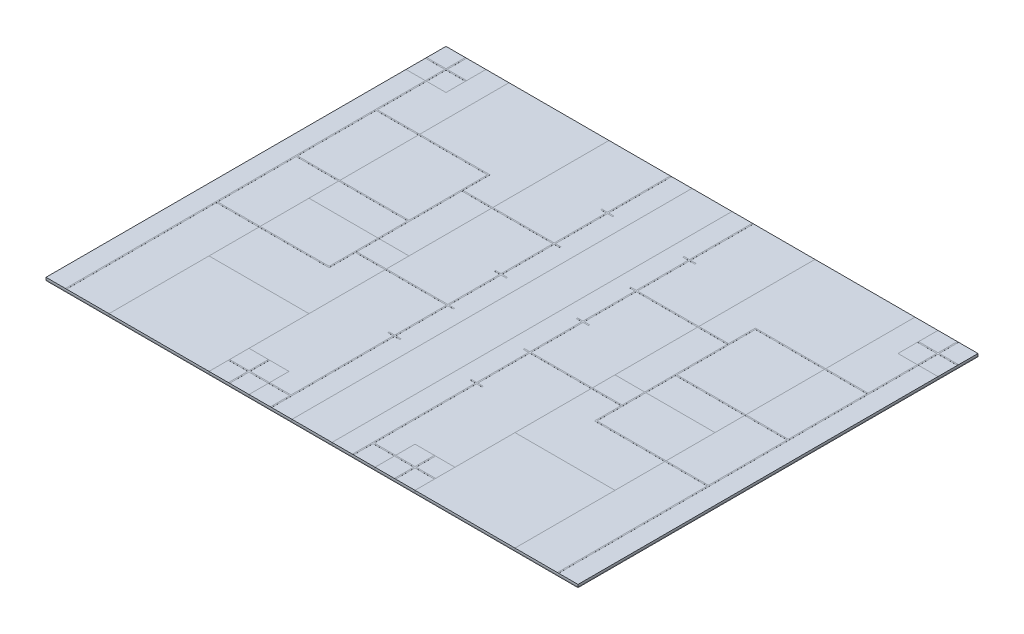
SolidWorks part; units mm, degrees
ref_plane "Front Plane" through (0, 0, 0) normal (0, 0, 1) x (1, 0, 0)
ref_plane "Top Plane" through (0, 0, 0) normal (0, 1, 0) x (1, 0, 0)
ref_plane "Right Plane" through (0, 0, 0) normal (1, 0, 0) x (0, 0, -1)
sketch "Sketch1" plane through (0, 0, 0) normal (0, 1, 0) x (1, 0, 0)
  line L1 (-6650, -5000) -> (6650, -5000)
  line L2 (-6650, -5000) -> (-6650, 5000)
  line L3 (-6650, 5000) -> (6650, 5000)
  line L4 (6650, -5000) -> (6650, 5000)
  line L5 (-6650, -5000) -> (6650, 5000) construction
  line L6 (-6650, 5000) -> (6650, -5000) construction
  point P0 (0, 0)
  dimension "D1" = 13300
  dimension "D2" = 10000
extrude "Boss-Extrude1" add sketch "Sketch1" along normal blind 20
sketch "Sketch3" plane through (0, 20, 0) normal (0, 1, 0) x (1, 0, 0)
  line L0 (6650, 5000) -> (-6650, 5000) construction
  line L1 (-6650, -5000) -> (-5075, -5000)
  line L2 (-6650, -5000) -> (-6650, 5000)
  line L3 (-6650, 5000) -> (-5075, 5000)
  line L4 (-5075, -5000) -> (-5075, 5000)
  dimension "D1" = 1575
extrude "Boss-Extrude2" add sketch "Sketch3" along normal blind 50 separate body
sketch "Sketch7" plane through (0, 20, 0) normal (0, 1, 0) x (1, 0, 0)
  line L1 (-5075, -5000) -> (-2575, -5000)
  line L2 (-5075, -5000) -> (-5075, -2500)
  line L3 (-5075, -2500) -> (-2575, -2500)
  line L4 (-2575, -5000) -> (-2575, -2500)
  dimension "D1" = 2500
  dimension "D2" = 2500
extrude "Boss-Extrude7" add sketch "Sketch7" along normal blind 50 separate body
sketch "Sketch8" plane through (0, 20, 0) normal (0, 1, 0) x (1, 0, 0)
  line L1 (-5075, -2500) -> (-2575, -2500)
  line L2 (-5075, -2500) -> (-5075, 0)
  line L3 (-5075, 0) -> (-2575, 0)
  line L4 (-2575, -2500) -> (-2575, 0)
  dimension "D1" = 2500
  dimension "D2" = 2500
extrude "Boss-Extrude8" add sketch "Sketch8" along normal blind 50 separate body
sketch "Sketch9" plane through (0, 20, 0) normal (0, 1, 0) x (1, 0, 0)
  line L0 (-5075, -5000) -> (-5075, 5000) construction
  line L1 (-5075, 0) -> (-2575, 0)
  line L2 (-5075, 0) -> (-5075, 5000)
  line L3 (-5075, 5000) -> (-2575, 5000)
  line L4 (-2575, 0) -> (-2575, 5000)
  line L5 (6650, 5000) -> (-6650, 5000) construction
  dimension "D1" = 2500
extrude "Boss-Extrude9" add sketch "Sketch9" along normal blind 50 separate body
sketch "Sketch10" plane through (0, 20, 0) normal (0, 1, 0) x (1, 0, 0)
  line L0 (6650, 5000) -> (-6650, 5000) construction
  line L1 (-2575, -5000) -> (-500, -5000)
  line L2 (-2575, -5000) -> (-2575, 5000)
  line L3 (-2575, 5000) -> (-500, 5000)
  line L4 (-500, -5000) -> (-500, 5000)
  dimension "D1" = 2075
extrude "Boss-Extrude10" add sketch "Sketch10" along normal blind 50 separate body
sketch "Sketch11" plane through (0, 20, 0) normal (0, 1, 0) x (1, 0, 0)
  line L0 (-6650, -5000) -> (6650, -5000) construction
  line L1 (-500, 5000) -> (500, 5000)
  line L2 (-500, 5000) -> (-500, -5000)
  line L3 (-500, -5000) -> (500, -5000)
  line L4 (500, 5000) -> (500, -5000)
  dimension "D1" = 1000
extrude "Boss-Extrude12" add sketch "Sketch11" along normal blind 50 separate body
sketch "Sketch12" plane through (0, 20, 0) normal (0, 1, 0) x (1, 0, 0)
  line L0 (-6650, -5000) -> (6650, -5000) construction
  line L1 (500, 5000) -> (2575, 5000)
  line L2 (500, 5000) -> (500, -5000)
  line L3 (500, -5000) -> (2575, -5000)
  line L4 (2575, 5000) -> (2575, -5000)
  dimension "D1" = 2075
extrude "Boss-Extrude13" add sketch "Sketch12" along normal blind 50 separate body
sketch "Sketch13" plane through (0, 20, 0) normal (0, 1, 0) x (1, 0, 0)
  line L1 (2575, 5000) -> (5075, 5000)
  line L2 (2575, 5000) -> (2575, 0)
  line L3 (2575, 0) -> (5075, 0)
  line L4 (5075, 5000) -> (5075, 0)
  dimension "D1" = 2500
  dimension "D2" = 5000
extrude "Boss-Extrude14" add sketch "Sketch13" along normal blind 50 separate body
sketch "Sketch14" plane through (0, 20, 0) normal (0, 1, 0) x (1, 0, 0)
  line L0 (2575, -5000) -> (2575, 5000) construction
  line L1 (2575, 0) -> (5075, 0)
  line L2 (2575, 0) -> (2575, -2500)
  line L3 (2575, -2500) -> (5075, -2500)
  line L4 (5075, 0) -> (5075, -2500)
  dimension "D1" = 2500
  dimension "D2" = 2500
extrude "Boss-Extrude15" add sketch "Sketch14" along normal blind 50 separate body
sketch "Sketch15" plane through (0, 20, 0) normal (0, 1, 0) x (1, 0, 0)
  line L0 (-6650, -5000) -> (6650, -5000) construction
  line L1 (2575, -2500) -> (5075, -2500)
  line L2 (2575, -2500) -> (2575, -5000)
  line L3 (2575, -5000) -> (5075, -5000)
  line L4 (5075, -2500) -> (5075, -5000)
  dimension "D1" = 2500
extrude "Boss-Extrude16" add sketch "Sketch15" along normal blind 50 separate body
sketch "Sketch16" plane through (0, 20, 0) normal (0, 1, 0) x (1, 0, 0)
  line L1 (6650, 5000) -> (5075, 5000)
  line L2 (6650, 5000) -> (6650, -5000)
  line L3 (6650, -5000) -> (5075, -5000)
  line L4 (5075, 5000) -> (5075, -5000)
extrude "Boss-Extrude17" add sketch "Sketch16" along normal blind 50 separate body
sketch "Sketch17" plane through (0, 70, 0) normal (0, 1, 0) x (1, 0, 0)
  line L1 (-6650, 5000) -> (-5650, 5000)
  line L2 (-6650, 5000) -> (-6650, 4000)
  line L3 (-6650, 4000) -> (-5650, 4000)
  line L4 (-5650, 5000) -> (-5650, 4000)
  dimension "D1" = 1000
  dimension "D2" = 1000
extrude "Cut-Extrude1" cut sketch "Sketch17" against normal blind 50
sketch "Sketch18" plane through (0, 20, 0) normal (0, 1, 0) x (1, 0, 0)
  line L1 (-6650, 5000) -> (-5650, 5000)
  line L2 (-6650, 5000) -> (-6650, 4000)
  line L3 (-6650, 4000) -> (-5650, 4000)
  line L4 (-5650, 5000) -> (-5650, 4000)
  dimension "D1" = 1000
  dimension "D2" = 1000
extrude "Boss-Extrude19" add sketch "Sketch18" along normal blind 50 separate body
sketch "Sketch19" plane through (0, 70, 0) normal (0, 1, 0) x (1, 0, 0)
  line L1 (-2575, -5000) -> (-1575, -5000)
  line L2 (-2575, -5000) -> (-2575, -4000)
  line L3 (-2575, -4000) -> (-1575, -4000)
  line L4 (-1575, -5000) -> (-1575, -4000)
  dimension "D1" = 1000
  dimension "D2" = 1000
extrude "Cut-Extrude2" cut sketch "Sketch19" against normal blind 50
sketch "Sketch20" plane through (0, 20, 0) normal (0, 1, 0) x (1, 0, 0)
  line L1 (-2575, -5000) -> (-1575, -5000)
  line L2 (-2575, -5000) -> (-2575, -4000)
  line L3 (-2575, -4000) -> (-1575, -4000)
  line L4 (-1575, -5000) -> (-1575, -4000)
extrude "Boss-Extrude20" add sketch "Sketch20" along normal blind 50 separate body
sketch "Sketch21" plane through (0, 70, 0) normal (0, 1, 0) x (1, 0, 0)
  line L1 (2575, -5000) -> (1575, -5000)
  line L2 (2575, -5000) -> (2575, -4000)
  line L3 (2575, -4000) -> (1575, -4000)
  line L4 (1575, -5000) -> (1575, -4000)
  dimension "D1" = 1000
  dimension "D2" = 1000
extrude "Cut-Extrude3" cut sketch "Sketch21" against normal blind 50
sketch "Sketch22" plane through (0, 20, 0) normal (0, 1, 0) x (1, 0, 0)
  line L1 (1575, -5000) -> (2575, -5000)
  line L2 (1575, -5000) -> (1575, -4000)
  line L3 (1575, -4000) -> (2575, -4000)
  line L4 (2575, -5000) -> (2575, -4000)
extrude "Boss-Extrude21" add sketch "Sketch22" along normal blind 50 separate body
sketch "Sketch23" plane through (0, 70, 0) normal (0, 1, 0) x (1, 0, 0)
  line L1 (6650, 5000) -> (5650, 5000)
  line L2 (6650, 5000) -> (6650, 4000)
  line L3 (6650, 4000) -> (5650, 4000)
  line L4 (5650, 5000) -> (5650, 4000)
  dimension "D1" = 1000
  dimension "D2" = 1000
extrude "Cut-Extrude4" cut sketch "Sketch23" against normal blind 50
sketch "Sketch24" plane through (0, 20, 0) normal (0, 1, 0) x (1, 0, 0)
  line L1 (5650, 4000) -> (6650, 4000)
  line L2 (5650, 4000) -> (5650, 5000)
  line L3 (5650, 5000) -> (6650, 5000)
  line L4 (6650, 4000) -> (6650, 5000)
extrude "Boss-Extrude22" add sketch "Sketch24" along normal blind 50 separate body
sketch "Sketch25" plane through (0, 70, 0) normal (0, 1, 0) x (1, 0, 0)
  line L0 (-6150, 5000) -> (-6135, 5000) construction
  line L1 (-5650, 5000) -> (-6650, 5000) construction
  line L2 (-6650, -5000) -> (-5075, -5000) construction
  line L3 (-6135, 5000) -> (-6165, 5000)
  line L4 (-6135, 5000) -> (-6135, 4515)
  line L5 (-6135, -5000) -> (-6165, -5000)
  line L6 (-6165, 5000) -> (-6165, 4515)
  line L7 (-6650, 4500) -> (-6650, 4515) construction
  line L8 (-6650, 5000) -> (-6650, 4000) construction
  line L9 (-5650, 4000) -> (-5650, 5000) construction
  line L10 (-6650, 4515) -> (-6165, 4515)
  line L11 (-6650, 4515) -> (-6650, 4485)
  line L12 (-6650, 4485) -> (-6165, 4485)
  line L13 (-5650, 4515) -> (-5650, 4485)
  line L14 (-6135, 4515) -> (-5650, 4515)
  line L15 (-6165, 4485) -> (-6165, -5000)
  line L16 (-6135, 4485) -> (-6135, 2767)
  line L17 (-6135, 4485) -> (-5650, 4485)
  line L18 (-6135, 5000) -> (-6135, 2767) construction
  line L19 (-6135, 2737) -> (-6135, 772)
  line L20 (-6135, 2767) -> (-3318, 2767)
  line L22 (-6135, 2737) -> (-3348, 2737)
  line L23 (-3318, 2767) -> (-3318, 2737)
  line L24 (-6135, -5000) -> (-6135, -1253) construction
  line L25 (-6135, -1253) -> (-6135, -5000)
  line L26 (-6135, -1253) -> (-3318, -1253)
  line L28 (-6135, -1223) -> (-3348, -1223)
  line L29 (-3318, -1253) -> (-3318, -1223)
  line L31 (-3318, 2737) -> (-3318, 2095)
  line L33 (-3348, 2737) -> (-3348, 772)
  line L34 (-6135, -1223) -> (-6135, 742) construction
  line L35 (-6135, 742) -> (-6135, -1223)
  line L36 (-6135, 742) -> (-3348, 742)
  line L38 (-6135, 772) -> (-3348, 772)
  line L40 (-3348, 742) -> (-3348, -1223)
  line L41 (-2075, -5000) -> (-2060, -5000) construction
  line L42 (-2575, -5000) -> (-1575, -5000) construction
  line L43 (-1575, -4000) -> (-2575, -4000) construction
  line L44 (-2060, -5000) -> (-2090, -5000)
  line L45 (-2060, -5000) -> (-2060, -4515)
  line L46 (-2060, -4000) -> (-2090, -4000)
  line L47 (-2090, -5000) -> (-2090, -4515)
  line L48 (-2575, -4500) -> (-2575, -4485) construction
  line L49 (-2575, -4000) -> (-2575, -5000) construction
  line L50 (-2060, -4485) -> (-1040, -4485)
  line L51 (-2575, -4485) -> (-2090, -4485)
  line L52 (-2575, -4485) -> (-2575, -4515)
  line L53 (-2575, -4515) -> (-2090, -4515)
  line L55 (-2060, -4515) -> (-1040, -4515)
  line L56 (-2060, -4485) -> (-2060, -4000)
  line L57 (-2090, -4485) -> (-2090, -4000)
  line L58 (-1575, -5000) -> (-500, -5000) construction
  line L59 (-1040, -5000) -> (-1010, -5000)
  line L60 (-1040, -5000) -> (-1040, -4515)
  line L61 (-1040, 5000) -> (-1010, 5000)
  line L62 (-1010, -5000) -> (-1010, -1925)
  line L63 (-500, 5000) -> (-2575, 5000) construction
  line L64 (-1040, -4485) -> (-1040, -1925)
  line L65 (-1040, -4485) -> (-1040, -1925) construction
  line L66 (-1040, -1925) -> (-1175, -1925)
  line L67 (-1175, -1925) -> (-1175, -1895)
  line L68 (-1175, -1895) -> (-1040, -1895)
  line L69 (-875, -1895) -> (-875, -1925)
  line L70 (-875, -1925) -> (-1010, -1925)
  line L71 (-1010, -1895) -> (-875, -1895)
  line L72 (-1040, -1895) -> (-1040, -595)
  line L73 (-1010, -1895) -> (-1010, -595)
  line L74 (-1040, -1895) -> (-1040, -595) construction
  line L75 (-1010, -595) -> (-875, -595) construction
  line L76 (-1040, -565) -> (-3318, -565)
  line L77 (-875, -595) -> (-1010, -595)
  line L78 (-875, -595) -> (-875, -565)
  line L79 (-875, -565) -> (-1010, -565)
  line L81 (-1040, -595) -> (-3318, -595)
  line L82 (-1040, -565) -> (-1040, 735)
  line L83 (-1010, -565) -> (-1010, 735)
  line L84 (-3318, -595) -> (-3318, -1223)
  line L85 (-1040, -565) -> (-1040, 735) construction
  line L86 (-1040, 735) -> (-1175, 735)
  line L87 (-1175, 735) -> (-1175, 765)
  line L88 (-1175, 765) -> (-1040, 765)
  line L89 (-875, 765) -> (-875, 735)
  line L91 (-875, 735) -> (-1010, 735)
  line L92 (-1010, 765) -> (-1010, 2065)
  line L93 (-1040, 765) -> (-1040, 2065)
  line L94 (-1010, 765) -> (-875, 765)
  line L95 (-1040, 765) -> (-1040, 2065) construction
  line L96 (-1040, 2065) -> (-3318, 2065)
  line L98 (-3318, 2095) -> (-1040, 2095)
  line L99 (-875, 2095) -> (-875, 2065)
  line L100 (-875, 2065) -> (-1010, 2065)
  line L101 (-1010, 2095) -> (-875, 2095)
  line L102 (-1040, 2095) -> (-1040, 3395)
  line L103 (-1010, 2095) -> (-1010, 3395)
  line L104 (-3318, 2065) -> (-3318, -565)
  line L105 (0, 5217.927) -> (0, -5658.4663) construction
  line L106 (1040, 765) -> (1040, 2065) construction
  line L107 (1040, -565) -> (1040, 735) construction
  line L108 (1010, -595) -> (875, -595) construction
  line L109 (1040, -1895) -> (1040, -595) construction
  line L110 (1040, -4485) -> (1040, -1925) construction
  line L111 (2575, -4500) -> (2575, -4485) construction
  line L112 (2075, -5000) -> (2060, -5000) construction
  line L113 (6135, -1223) -> (6135, 742) construction
  line L114 (6135, -5000) -> (6135, -1253) construction
  line L115 (6135, 5000) -> (6135, 2767) construction
  line L116 (6650, 4500) -> (6650, 4515) construction
  line L117 (6150, 5000) -> (6135, 5000) construction
  line L118 (3318, 2065) -> (3318, -565)
  line L119 (1010, 2095) -> (1010, 3395)
  line L120 (1040, 2095) -> (1040, 3395)
  line L121 (1010, 2095) -> (875, 2095)
  line L122 (875, 2065) -> (1010, 2065)
  line L123 (875, 2095) -> (875, 2065)
  line L124 (3318, 2095) -> (1040, 2095)
  line L125 (1040, 2065) -> (3318, 2065)
  line L126 (1010, 765) -> (875, 765)
  line L127 (1040, 765) -> (1040, 2065)
  line L128 (1010, 765) -> (1010, 2065)
  line L129 (875, 735) -> (1010, 735)
  line L130 (875, 765) -> (875, 735)
  line L131 (1175, 765) -> (1040, 765)
  line L132 (1175, 735) -> (1175, 765)
  line L133 (1040, 735) -> (1175, 735)
  line L134 (3318, -595) -> (3318, -1223)
  line L135 (1010, -565) -> (1010, 735)
  line L136 (1040, -565) -> (1040, 735)
  line L137 (1040, -595) -> (3318, -595)
  line L138 (875, -565) -> (1010, -565)
  line L139 (875, -595) -> (875, -565)
  line L140 (875, -595) -> (1010, -595)
  line L141 (1040, -565) -> (3318, -565)
  line L142 (1010, -1895) -> (1010, -595)
  line L143 (1040, -1895) -> (1040, -595)
  line L144 (1010, -1895) -> (875, -1895)
  line L145 (875, -1925) -> (1010, -1925)
  line L146 (875, -1895) -> (875, -1925)
  line L147 (1175, -1895) -> (1040, -1895)
  line L148 (1175, -1925) -> (1175, -1895)
  line L149 (1040, -1925) -> (1175, -1925)
  line L150 (1040, -4485) -> (1040, -1925)
  line L151 (1010, -5000) -> (1010, -1925)
  line L152 (1040, 5000) -> (1010, 5000)
  line L153 (1040, -5000) -> (1040, -4515)
  line L154 (1040, -5000) -> (1010, -5000)
  line L155 (2090, -4485) -> (2090, -4000)
  line L156 (2060, -4485) -> (2060, -4000)
  line L157 (2060, -4515) -> (1040, -4515)
  line L158 (2575, -4515) -> (2090, -4515)
  line L159 (2575, -4485) -> (2575, -4515)
  line L160 (2575, -4485) -> (2090, -4485)
  line L161 (2060, -4485) -> (1040, -4485)
  line L162 (2090, -5000) -> (2090, -4515)
  line L163 (2060, -4000) -> (2090, -4000)
  line L164 (2060, -5000) -> (2060, -4515)
  line L165 (2060, -5000) -> (2090, -5000)
  line L166 (3348, 742) -> (3348, -1223)
  line L167 (6135, 772) -> (3348, 772)
  line L168 (6135, 742) -> (3348, 742)
  line L169 (6135, 742) -> (6135, -1223)
  line L170 (3348, 2737) -> (3348, 772)
  line L171 (3318, 2737) -> (3318, 2095)
  line L172 (3318, -1253) -> (3318, -1223)
  line L173 (6135, -1223) -> (3348, -1223)
  line L174 (6135, -1253) -> (3318, -1253)
  line L175 (6135, -1253) -> (6135, -5000)
  line L176 (3318, 2767) -> (3318, 2737)
  line L177 (6135, 2737) -> (3348, 2737)
  line L178 (6135, 2767) -> (3318, 2767)
  line L179 (6135, 2737) -> (6135, 772)
  line L180 (6135, 4485) -> (5650, 4485)
  line L181 (6135, 4485) -> (6135, 2767)
  line L182 (6165, 4485) -> (6165, -5000)
  line L183 (6135, 4515) -> (5650, 4515)
  line L184 (5650, 4515) -> (5650, 4485)
  line L185 (6650, 4485) -> (6165, 4485)
  line L186 (6650, 4515) -> (6650, 4485)
  line L187 (6650, 4515) -> (6165, 4515)
  line L188 (6165, 5000) -> (6165, 4515)
  line L189 (6135, -5000) -> (6165, -5000)
  line L190 (6135, 5000) -> (6135, 4515)
  line L191 (6135, 5000) -> (6165, 5000)
  line L192 (-1040, 2095) -> (-1040, 3395) construction
  line L193 (-1040, 3395) -> (-1175, 3395)
  line L194 (-1175, 3395) -> (-1175, 3425)
  line L195 (-1175, 3425) -> (-1040, 3425)
  line L196 (-875, 3425) -> (-875, 3395)
  line L197 (-875, 3395) -> (-1010, 3395)
  line L198 (-1010, 3425) -> (-875, 3425)
  line L199 (-1010, 3425) -> (-1010, 5000)
  line L200 (-1040, 3425) -> (-1040, 5000)
  line L201 (1010, 3425) -> (875, 3425)
  line L202 (875, 3395) -> (1010, 3395)
  line L203 (875, 3425) -> (875, 3395)
  line L204 (1175, 3395) -> (1175, 3425)
  line L205 (1040, 3395) -> (1175, 3395)
  line L206 (1175, 3425) -> (1040, 3425)
  line L207 (1040, 3425) -> (1040, 5000)
  line L208 (1010, 3425) -> (1010, 5000)
  line M56 (-6650, 5000) -> (-6650, 4000)
  line M57 (-6650, 4000) -> (-5650, 4000)
  line M58 (-5650, 4000) -> (-5650, 5000)
  line M59 (-5650, 5000) -> (-6650, 5000)
  dimension "D1" = 15
  dimension "D2" = 30
  dimension "D3" = 15
  dimension "D4" = 30
  dimension "D5" = 2233
  dimension "D6" = 30
  dimension "D7" = 743
  dimension "D8" = 3747
  dimension "D9" = 30
  dimension "D10" = 30
  dimension "D11" = 2787
  dimension "D12" = 3960
  dimension "D13" = 1965
  dimension "D14" = 30
  dimension "D15" = 15
  dimension "D16" = 30
  dimension "D17" = 15
  dimension "D18" = 30
  dimension "D19" = 2560
  dimension "D20" = 30
  dimension "D21" = 535
  dimension "D22" = 135
  dimension "D23" = 30
  dimension "D24" = 135
  dimension "D25" = 1300
  dimension "D26" = 165
  dimension "D27" = 30
  dimension "D28" = 1300
  dimension "D29" = 135
  dimension "D30" = 135
  dimension "D31" = 30
  dimension "D32" = 1300
  dimension "D33" = 165
  dimension "D34" = 1300
  dimension "D35" = 30
  dimension "D36" = 30
  dimension "D37" = 30
  dimension "D38" = 165
  dimension "D39" = 135
  dimension "D40" = 30
extrude "Boss-Extrude31" add sketch "Sketch25" along normal blind 1 separate body contours L101 L103 L61 L102 L98 L31 L23 L20 L16 L15 L5 L25 L26 L29 L84 L81 L72 L68 L67 L66 L64 L50 L56 L46 L57 L51 L52 L53 L47 L44 L45 L55 L60 L59 L62 L70 L69 L71 L73 L77 L78 L79 L83 L91 L89 L94 L92 L100 L99 M57 | L16 L17 L14 L4 L6 L10 L12 L15 M58 M59 M56 M57 | L191 L190 L183 L184 L180 L181 L178 L176 L171 L124 L120 L152 L119 L121 L123 L122 L128 L126 L130 L129 L135 L138 L139 L140 L142 L144 L146 L145 L151 L154 L153 L157 L164 L165 L162 L158 L159 L160 L155 L163 L156 L161 L150 L149 L148 L147 L143 L137 L134 L172 L174
